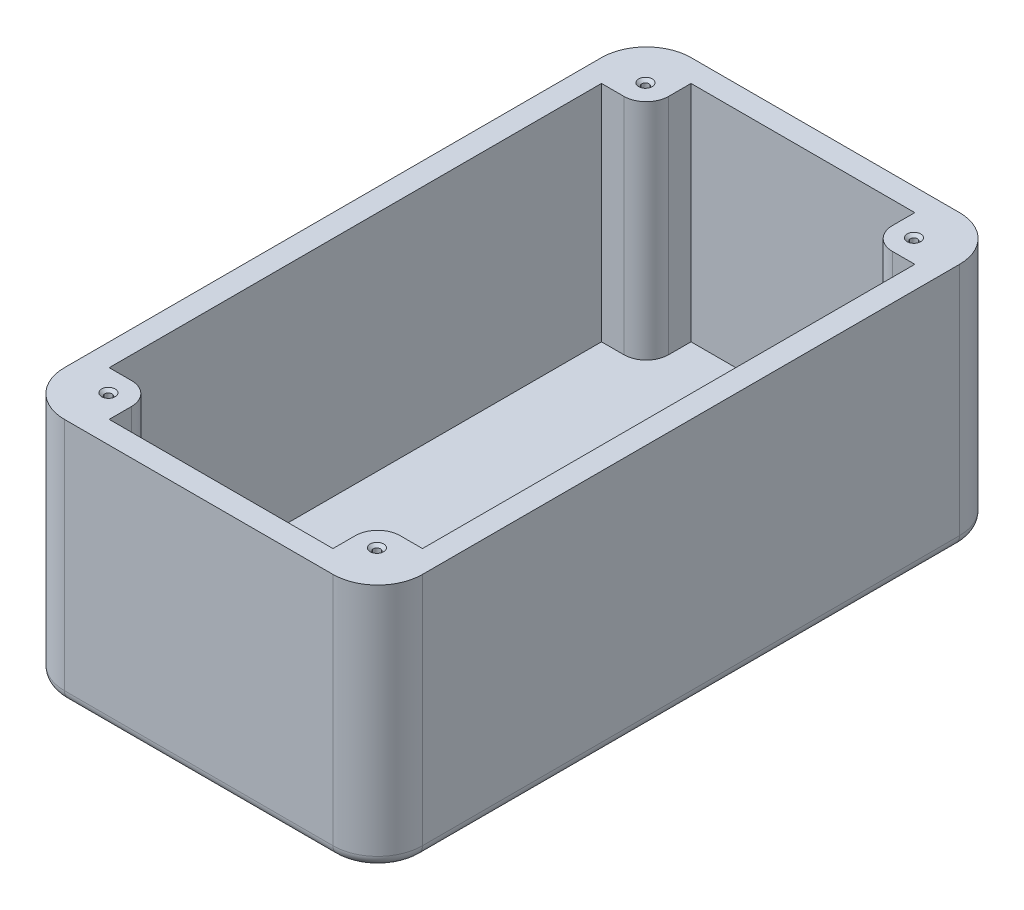
SolidWorks part; units mm, degrees
ref_plane "Front Plane" through (0, 0, 0) normal (0, 0, 1) x (1, 0, 0)
ref_plane "Top Plane" through (0, 0, 0) normal (0, 1, 0) x (1, 0, 0)
ref_plane "Right Plane" through (0, 0, 0) normal (1, 0, 0) x (0, 0, -1)
sketch "Sketch2" plane through (0, 0, 0) normal (0, 1, 0) x (1, 0, 0)
  line L1 (-40, -70) -> (40, -70)
  line L2 (-40, -70) -> (-40, 70)
  line L3 (-40, 70) -> (40, 70)
  line L4 (40, -70) -> (40, 70)
  line L5 (-40, -70) -> (40, 70) construction
  line L6 (-40, 70) -> (40, -70) construction
  point P0 (0, 0)
  dimension "D1" = 80
  dimension "D2" = 140
extrude "Boss-Extrude1" add sketch "Sketch2" along normal blind 50
shell "Shell1" thickness 5
sketch "Sketch3" plane through (0, 50, 0) normal (0, 1, 0) x (1, 0, 0)
  line L1 (-40, -70) -> (40, -70)
  line L2 (-40, -70) -> (-40, 70)
  line L3 (-40, 70) -> (40, 70)
  line L4 (40, -70) -> (40, 70)
  line L5 (-40, -70) -> (40, 70) construction
  line L6 (-40, 70) -> (40, -70) construction
  line L7 (-35, -65) -> (35, -65)
  line L8 (-35, -65) -> (-35, 65)
  line L9 (-35, 65) -> (35, 65)
  line L10 (35, -65) -> (35, 65)
  line L11 (-35, -65) -> (35, 65) construction
  line L12 (-35, 65) -> (35, -65) construction
  point P0 (0, 0)
  point P7 (0, 0)
extrude "Boss-Extrude2" add sketch "Sketch3" along normal blind 5
sketch "Sketch4" plane through (0, 55, 0) normal (0, 1, 0) x (1, 0, 0)
  line L0 (-35, -65) -> (-35, -55)
  line L1 (-35, 65) -> (-35, -65) construction
  line L2 (-35, -65) -> (-25, -65)
  line L3 (-35, -65) -> (35, -65) construction
  line L4 (-35, -55) -> (-30, -55)
  line L5 (-25, -65) -> (-25, -60)
  line L6 (30, -55) -> (35, -55)
  line L7 (35, -65) -> (35, 65) construction
  line L8 (35, -55) -> (35, -65)
  line L9 (35, -65) -> (25, -65)
  line L10 (25, -65) -> (25, -60)
  line L11 (25, 60) -> (25, 65)
  line L12 (35, 65) -> (-35, 65) construction
  line L13 (25, 65) -> (35, 65)
  line L14 (35, 65) -> (35, 55)
  line L15 (35, -65) -> (35, 65) construction
  line L16 (35, 55) -> (30, 55)
  line L17 (-30, 55) -> (-35, 55)
  line L18 (-35, 65) -> (-35, -65) construction
  line L19 (-35, 55) -> (-35, 65)
  line L20 (-35, 65) -> (-25, 65)
  line L21 (-25, 65) -> (-25, 60)
  arc A1 (-30, -55) -> (-25, -60) centre (-30, -60) cw
  arc A2 (25, -60) -> (30, -55) centre (30, -60) cw
  arc A3 (25, 60) -> (30, 55) centre (30, 60) ccw
  arc A4 (-30, 55) -> (-25, 60) centre (-30, 60) ccw
  dimension "D1" = 10
  dimension "D2" = 10
  dimension "D3" = 5
  dimension "D4" = 5
  dimension "D5" = 5
  dimension "D6" = 10
  dimension "D7" = 10
  dimension "D8" = 5
  dimension "D9" = 10
  dimension "D10" = 10
  dimension "D11" = 5
  dimension "D12" = 5
  dimension "D13" = 5
  dimension "D14" = 10
  dimension "D15" = 10
  dimension "D16" = 5
extrude "Boss-Extrude3" add sketch "Sketch4" against normal up to next
hole_wizard "CSK for #0 Flat Head Machine Screw (100)1" positions "Sketch7" profile "Sketch8" countersink size "#0" standard "ANSI Inch"
sketch "Sketch7" plane through (0, 55, 0) normal (0, 1, 0) x (1, 0, 0)
  point P0 (-30.2163, -59.9579)
  point P2 (29.7724, -59.9579)
  point P4 (29.7724, 60.0284)
  point P6 (-30.2163, 60.0284)
sketch "Sketch8" plane through (-30.2163, 55, 59.9579) normal (1, 0, 0) x (0, 0, 1)
  line L0 (0, 0) -> (0, 10.4846)
  line L1 (0, 10.4846) -> (0.8064, 10)
  line L2 (0.8064, 10) -> (0.8064, 0.5914)
  line L3 (0.8064, 0.5914) -> (1.5113, 0)
  line L5 (1.5113, 0) -> (0, 0)
  line L6 (-0.8064, 0.5914) -> (-1.5113, 0) construction
  line L10 (0, 10.4846) -> (-0.8064, 10) construction
  line L11 (0, -6.35) -> (0, 107.95) construction
  dimension "Hole Dia." = 1.6129
  dimension "Hole Depth" = 10
  dimension "Near C'Sink Dia." = 3.0226
  dimension "Near C'Sink Angle" = 100
  dimension "Drill Angle" = 118
fillet "Fillet1" radius 10 4 edges at (-40, 27.5, -70) (40, 27.5, -70) (-40, 27.5, 70) (40, 27.5, 70)
fillet "Fillet2" radius 2.5 8 edges at (-37.0711, 0, 67.0711) (0, 0, 70) (37.0711, 0, 67.0711) (40, 0, 0) (37.0711, 0, -67.0711) (0, 0, -70) (-37.0711, 0, -67.0711) (-40, 0, 0)
